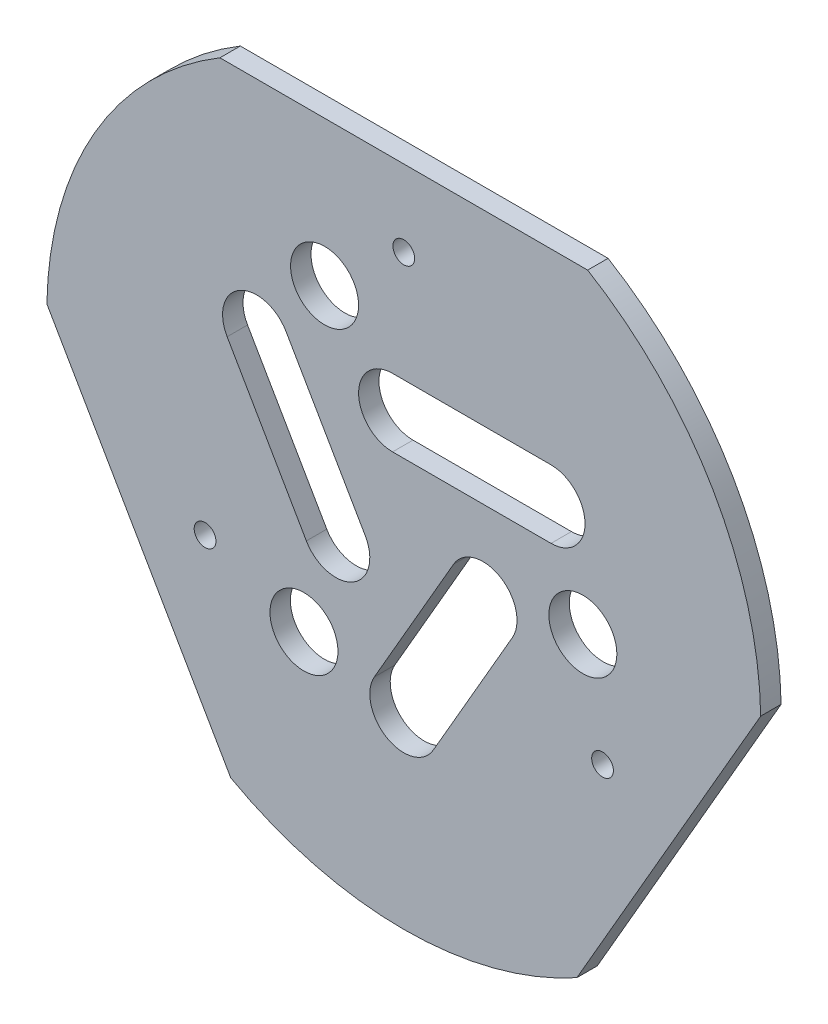
SolidWorks part; units mm, degrees
ref_plane "前视基准面" through (0, 0, 0) normal (0, 0, 1) x (1, 0, 0)
ref_plane "上视基准面" through (0, 0, 0) normal (0, 1, 0) x (1, 0, 0)
ref_plane "右视基准面" through (0, 0, 0) normal (1, 0, 0) x (0, 0, -1)
sketch "草图1" plane through (0, 0, 0) normal (0, 0, 1) x (1, 0, 0)
  line L1 (25.4503, -45.9187) -> (52.492, 0.9187)
  line L2 (27.0416, 45) -> (-27.0416, 45)
  line L3 (-52.492, 0.9187) -> (-25.4503, -45.9187)
  circle A1 centre (0, 0) radius 45 construction
  arc A2 (-27.0416, 45) -> (-52.492, 0.9187) centre (0, 0) ccw
  arc A3 (-25.4503, -45.9187) -> (25.4503, -45.9187) centre (0, 0) ccw
  arc A4 (52.492, 0.9187) -> (27.0416, 45) centre (0, 0) ccw
  circle A5 centre (0, 0) radius 33.75 construction
  circle A6 centre (0, 0) radius 25 construction
  circle A7 centre (0, 33.75) radius 1.6
  circle A8 centre (29.2284, -16.875) radius 1.6
  circle A9 centre (-29.2284, -16.875) radius 1.6
  circle A10 centre (0, -25) radius 5
  circle A11 centre (-21.6506, 12.5) radius 5
  circle A12 centre (21.6506, 12.5) radius 5
  point P21 (0, 0)
  point P28 (0, 0)
  dimension "D1" = 90
  dimension "D2" = 105
  dimension "D3" = 50
  dimension "D4" = 67.5
  dimension "D5" = 3.2
  dimension "D7" = 10
  dimension "D6" = 3
  dimension "D8" = 3
extrude "凸台-拉伸1" add sketch "草图1" along normal mid plane 3
sketch "草图2" plane through (0, 0, 1.5) normal (0, 0, 1) x (1, 0, 0)
  line L0 (-21.6506, 12.5) -> (-10, -7.6795) construction
  line L1 (-17.3205, 15) -> (-5.6699, -5.1795)
  line L2 (-25.9808, 10) -> (-14.3301, -10.1795)
  line L3 (-10, -7.6795) -> (0, -25) construction
  arc A0 (-17.3205, 15) -> (-25.9808, 10) centre (-21.6506, 12.5) ccw
  arc A1 (-14.3301, -10.1795) -> (-5.6699, -5.1795) centre (-10, -7.6795) ccw
  circle A2 centre (-21.6506, 12.5) radius 5 construction
  point P3 (-15.8253, 2.4103)
  dimension "D1" = 20
extrude "切除-拉伸1" cut sketch "草图2" against normal through all
pattern_circular "阵列(圆周)1" count 3 over 360 about axis through (0, 0, 0) along (0, 0, 1) of "切除-拉伸1"
sketch "草图3" plane through (0, 0, 1.5) normal (0, 0, 1) x (1, 0, 0)
  line L0 (-21.6506, 12.5) -> (-11.6506, 23.6803) construction
  line L2 (-11.6506, 23.6803) -> (-1.6506, 12.5) construction
  circle A0 centre (-11.6506, 23.6803) radius 5
  arc A6 (-1.6506, 17.5) -> (-1.6506, 7.5) centre (-1.6506, 12.5) ccw construction
  arc A8 (-17.3205, 15) -> (-25.9808, 10) centre (-21.6506, 12.5) ccw construction
  dimension "D1" = 15
extrude "切除-拉伸3" cut sketch "草图3" against normal through all
pattern_circular "阵列(圆周)3" count 3 over 360 about axis through (0, 0, 0) along (0, 0, 1) of "切除-拉伸3"
